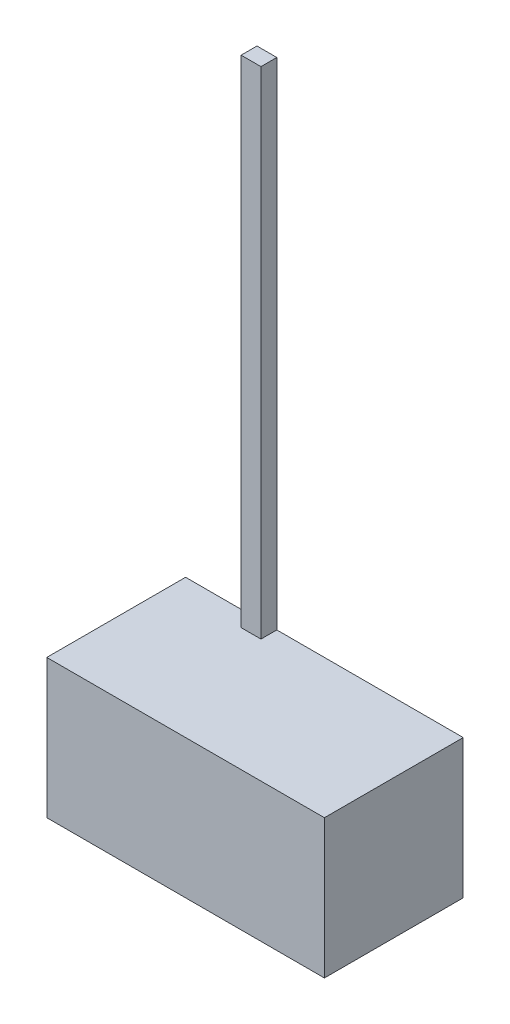
SolidWorks part; units mm, degrees
ref_plane "Front Plane" through (0, 0, 0) normal (0, 0, 1) x (1, 0, 0)
ref_plane "Top Plane" through (0, 0, 0) normal (0, 1, 0) x (1, 0, 0)
ref_plane "Right Plane" through (0, 0, 0) normal (1, 0, 0) x (0, 0, -1)
sketch "Sketch1" plane through (0, 0, 0) normal (0, 0, 1) x (1, 0, 0)
  line L0 (1780, -200) -> (1780, -1450)
  line L1 (1780, -1450) -> (1830, -1450)
  line L2 (1830, -1450) -> (1830, -200)
  line L3 (1830, -200) -> (1780, -200)
extrude "Boss-Extrude1" add sketch "Sketch1" along normal blind 40 separate body
sketch "Sketch2" plane through (0, 0, 0) normal (0, 0, 1) x (1, 0, 0)
  line L0 (1600, -1450) -> (1600, -1800)
  line L1 (1600, -1800) -> (2300, -1800)
  line L2 (2300, -1800) -> (2300, -1450)
  line L3 (2300, -1450) -> (1600, -1450)
extrude "Boss-Extrude2" add sketch "Sketch2" along normal blind 350 separate body
